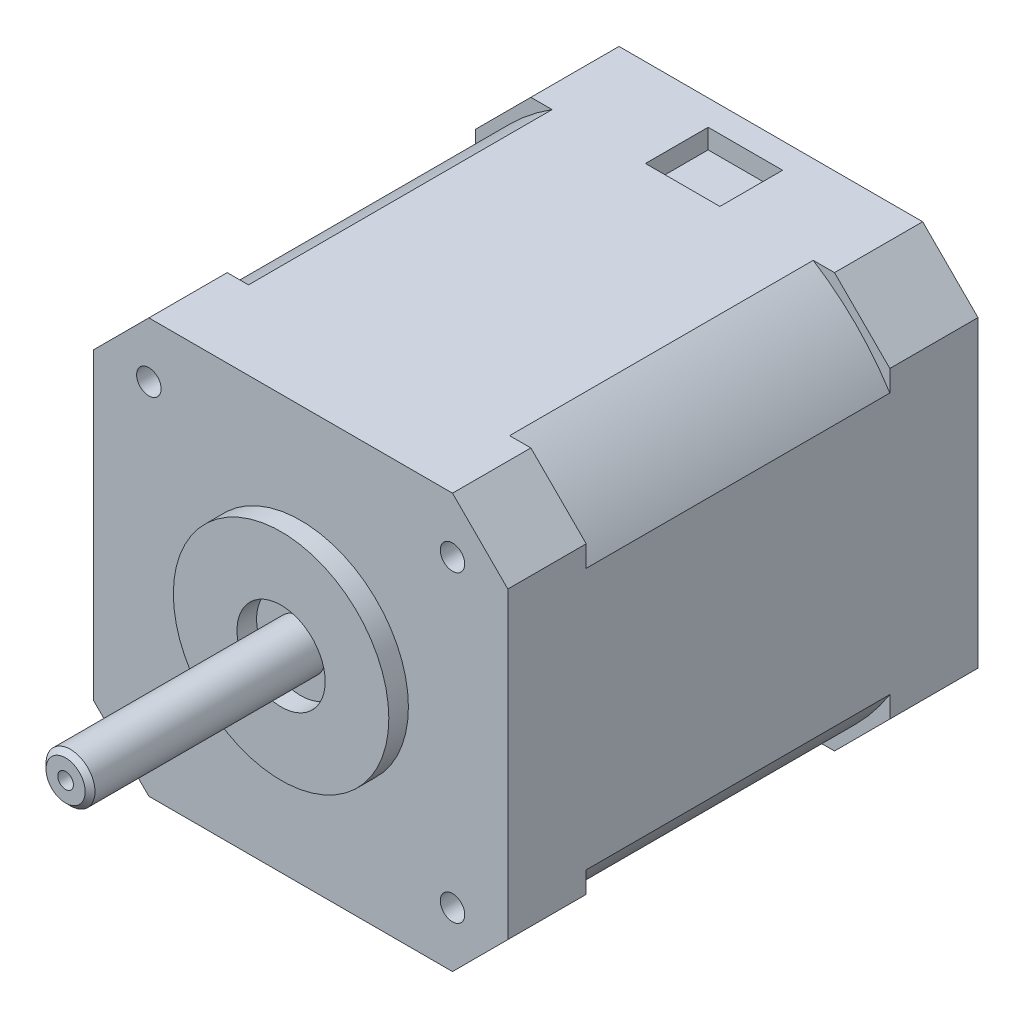
SolidWorks part; units mm, degrees
ref_plane "Front Plane" through (0, 0, 0) normal (0, 0, 1) x (1, 0, 0)
ref_plane "Top Plane" through (0, 0, 0) normal (0, 1, 0) x (1, 0, 0)
ref_plane "Right Plane" through (0, 0, 0) normal (1, 0, 0) x (0, 0, -1)
sketch "Sketch2" plane through (0, 0, 0) normal (0, 0, 1) x (1, 0, 0)
  line L0 (-15.5, 21.15) -> (15.5, 21.15)
  line L1 (15.5, 21.15) -> (21.15, 15.5)
  line L2 (21.15, 15.5) -> (21.15, -15.5)
  line L3 (21.15, -15.5) -> (15.5, -21.15)
  line L4 (15.5, -21.15) -> (-15.5, -21.15)
  line L5 (-15.5, -21.15) -> (-21.15, -15.5)
  line L6 (-21.15, -15.5) -> (-21.15, 15.5)
  line L7 (-21.15, 15.5) -> (-15.5, 21.15)
  point P8 (0, 21.15)
  point P11 (0, -21.15)
  point P13 (-21.15, 0)
  point P14 (21.15, 0)
  dimension "D1" = 42.3
  dimension "D2" = 42.3
  dimension "D3" = 31
extrude "Boss-Extrude1" add sketch "Sketch2" against normal blind 8
ref_plane "Plane1" through (0, 0, -48) normal (0, 0, 1) x (1, 0, 0)
sketch "Sketch3" plane through (0, 0, -48) normal (0, 0, 1) x (1, 0, 0)
  line L0 (-15.5, 21.15) -> (15.5, 21.15)
  line L1 (15.5, 21.15) -> (21.15, 15.5)
  line L2 (21.15, 15.5) -> (21.15, -15.5)
  line L3 (21.15, -15.5) -> (15.5, -21.15)
  line L4 (15.5, -21.15) -> (-15.5, -21.15)
  line L5 (-15.5, -21.15) -> (-21.15, -15.5)
  line L6 (-21.15, -15.5) -> (-21.15, 15.5)
  line L7 (-21.15, 15.5) -> (-15.5, 21.15)
  point P9 (21.15, 0)
  point P11 (-21.15, 0)
  point P12 (0, 21.15)
  point P13 (0, -21.15)
  dimension "D1" = 42.3
  dimension "D2" = 42.3
  dimension "D3" = 31
extrude "Boss-Extrude2" add sketch "Sketch3" along normal blind 9 separate body contours L2 L3 L4 L5 L6 L7 L0 L1
sketch "Sketch4" plane through (0, 0, -8) normal (0, 0, -1) x (-1, 0, 0)
  line L1 (-13.3296, 21.15) -> (13.3296, 21.15)
  line L2 (-21.15, 13.3296) -> (-21.15, -13.3296)
  line L3 (-13.3296, -21.15) -> (13.3296, -21.15)
  line L4 (21.15, 13.3296) -> (21.15, -13.3296)
  arc A0 (-13.3296, 21.15) -> (-21.15, 13.3296) centre (0, 0) ccw
  arc A1 (-21.15, -13.3296) -> (-13.3296, -21.15) centre (0, 0) ccw
  arc A2 (13.3296, -21.15) -> (21.15, -13.3296) centre (0, 0) ccw
  arc A3 (21.15, 13.3296) -> (13.3296, 21.15) centre (0, 0) ccw
  point P0 (-21.15, 0)
  point P1 (21.15, 0)
  dimension "D1" = 25
  dimension "D2" = 42.3
extrude "Boss-Extrude3" add sketch "Sketch4" along normal up to next
sketch "Sketch5" plane through (0, 0, 0) normal (0, 0, 1) x (1, 0, 0)
  circle A0 centre (0, 0) radius 11
  circle A2 centre (0, 0) radius 4.5
  dimension "D1" = 22
  dimension "D2" = 9
extrude "Boss-Extrude4" add sketch "Sketch5" along normal blind 2
sketch "Sketch6" plane through (0, 0, 0) normal (0, 0, 1) x (1, 0, 0)
  line L0 (-15.5, 15.5) -> (15.5, 15.5) construction
  line L1 (15.5, 15.5) -> (15.5, -15.5) construction
  circle A0 centre (-15.5, 15.5) radius 1.25
  circle A1 centre (15.5, 15.5) radius 1.25
  circle A2 centre (15.5, -15.5) radius 1.25
  circle A3 centre (-15.5, -15.5) radius 1.25
  point P8 (0, 15.5)
  point P9 (15.5, 0)
  dimension "D3" = 2.5
  dimension "D1" = 31
  dimension "D2" = 31
extrude "Cut-Extrude1" cut sketch "Sketch6" against normal through all
sketch "Sketch7" plane through (0, 0, 0) normal (0, 0, 1) x (1, 0, 0)
  circle A0 centre (0, 0) radius 2.5
  dimension "D1" = 5
extrude "Boss-Extrude5" add sketch "Sketch7" along normal blind 24
chamfer "Chamfer1" distance 0.5 angle 45 1 edges at (2.5, 0, 24)
sketch "Sketch8" plane through (0, 0, 24) normal (0, 0, 1) x (1, 0, 0)
  circle A0 centre (0, 0) radius 0.8
  dimension "D1" = 1.6
extrude "Cut-Extrude2" cut sketch "Sketch8" against normal blind 2.5
sketch "Sketch9" plane through (0, 0, -48) normal (0, 0, -1) x (-1, 0, 0)
  circle A0 centre (-15.5, 15.5) radius 3
  circle A1 centre (15.5, 15.5) radius 3
  circle A2 centre (15.5, -15.5) radius 3
  circle A3 centre (-15.5, -15.5) radius 3
  dimension "D1" = 6
extrude "Cut-Extrude3" cut sketch "Sketch9" against normal blind 2.5
sketch "Sketch18" plane through (0, 0, -48) normal (0, 0, -1) x (-1, 0, 0)
  circle A0 centre (0, 0) radius 4.5
  dimension "D1" = 9
sketch "Sketch23" plane through (0, 21.15, 0) normal (0, 1, 0) x (1, 0, 0)
  line L0 (-13.3296, 39) -> (13.3296, 39) construction
  line L1 (-3.8, 45.4) -> (3.8, 45.4)
  line L2 (-3.8, 45.4) -> (-3.8, 39)
  line L3 (-3.8, 39) -> (3.8, 39)
  line L4 (3.8, 45.4) -> (3.8, 39)
  point P9 (0, 39)
  point P10 (0, 45.4)
  dimension "D1" = 7.6
  dimension "D2" = 6.4
extrude "Cut-Extrude5" cut sketch "Sketch23" against normal blind 2
extrude "Cut-Extrude4" cut sketch "Sketch18" against normal blind 3.5
equation "\"mounting_holes_space\"= 31mm"
equation "\"width\"= 42.3mm"
equation "\"deepness\"= 48mm"
equation "\"shaft_length\"= 24mm"
equation "\"shaft_diameter\"= 5mm"
equation "\"mounting_OD\"= 22mm"
equation "\"mounting_length\"= 2mm"
equation "\"front\"= 8mm"
equation "\"back\"= 9mm"
equation "\"D1@Sketch2\"=\"width\""
equation "\"D2@Sketch2\"=\"width\""
equation "\"side\"= 31mm"
equation "\"D3@Sketch2\"=\"side\""
equation "\"D1@Boss-Extrude1\"=\"front\""
equation "\"D1@Plane1\"=\"deepness\""
equation "\"D1@Sketch3\"=\"width\""
equation "\"D2@Sketch3\"=\"width\""
equation "\"D3@Sketch3\"=\"side\""
equation "\"D1@Boss-Extrude2\"=\"back\""
equation "\"diameter\"= 50mm"
equation "\"D2@Sketch4\"=\"width\""
equation "\"D1@Sketch5\"=\"mounting_OD\""
equation "\"D1@Boss-Extrude4\"=\"mounting_length\""
equation "\"D1@Sketch6\"=\"mounting_holes_space\""
equation "\"D2@Sketch6\"=\"mounting_holes_space\""
equation "\"D1@Sketch7\"=\"shaft_diameter\""
equation "\"D1@Boss-Extrude5\"=\"shaft_length\""
